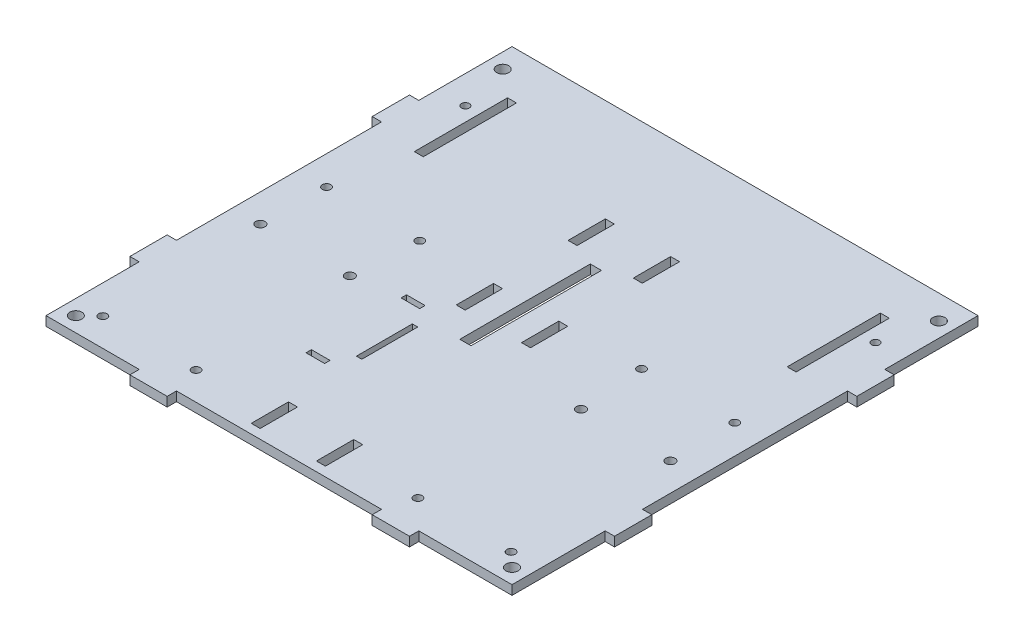
SolidWorks part; units mm, degrees
ref_plane "Front Plane" through (0, 0, 0) normal (0, 0, 1) x (1, 0, 0)
ref_plane "Top Plane" through (0, 0, 0) normal (0, 1, 0) x (1, 0, 0)
ref_plane "Right Plane" through (0, 0, 0) normal (1, 0, 0) x (0, 0, -1)
sketch "Sketch1" plane through (0, 0, 0) normal (0, 1, 0) x (1, 0, 0)
  line L0 (144.9, 25) -> (144.9, 5)
  line L1 (144.9, 5) -> (140.1, 5)
  line L2 (140.1, 25) -> (144.9, 25)
  line L3 (140.1, 5) -> (140.1, 25)
  line L4 (109.9, 5) -> (109.9, 25)
  line L5 (109.9, 25) -> (105.1, 25)
  line L6 (105.1, 25) -> (105.1, 5)
  line L7 (105.1, 5) -> (109.9, 5)
  line L8 (87, 52.4842) -> (97, 52.4842)
  line L9 (97, 55.3842) -> (97, 52.4842)
  line L10 (87, 55.3842) -> (97, 55.3842)
  line L11 (87, 52.4842) -> (87, 55.3842)
  line L12 (105, 64.4342) -> (102.1, 64.4342)
  line L13 (105, 64.4342) -> (105, 94.4342)
  line L14 (102.1, 94.4342) -> (102.1, 64.4342)
  line L15 (102.1, 94.4342) -> (105, 94.4342)
  line L16 (97, 106.3842) -> (97, 103.4842)
  line L17 (97, 106.3842) -> (87, 106.3842)
  line L18 (87, 103.4842) -> (97, 103.4842)
  line L19 (87, 103.4842) -> (87, 106.3842)
  line L20 (109.9, 135) -> (105.1, 135)
  line L21 (109.9, 115) -> (109.9, 135)
  line L22 (105.1, 135) -> (105.1, 115)
  line L23 (105.1, 115) -> (109.9, 115)
  line L24 (144.9, 115) -> (140.1, 115)
  line L25 (140.1, 115) -> (140.1, 135)
  line L26 (144.9, 135) -> (144.9, 115)
  line L27 (140.1, 135) -> (144.9, 135)
  line L28 (227.4, 175) -> (227.4, 225)
  line L29 (222.6, 175) -> (222.6, 225)
  line L30 (227.4, 225) -> (222.6, 225)
  line L31 (222.6, 175) -> (227.4, 175)
  line L32 (125, 100) -> (125, 170) construction
  line L33 (122, 170) -> (128, 170)
  line L34 (122, 170) -> (122, 100)
  line L35 (122, 100) -> (128, 100)
  line L36 (22.6, 225) -> (27.4, 225)
  line L37 (27.4, 225) -> (27.4, 175)
  line L38 (22.6, 175) -> (22.6, 225)
  line L39 (27.4, 175) -> (22.6, 175)
  line L40 (250, 250) -> (0, 250)
  line L41 (0, 250) -> (0, 0)
  line L42 (0, 0) -> (250, 0)
  line L43 (250, 0) -> (250, 250)
  line L44 (128, 170) -> (128, 100)
  dimension "D2" = 22.6
  dimension "D3" = 5.1
  dimension "D4" = 10
  dimension "D5" = 102.1
  dimension "D6" = 2.9
  dimension "D7" = 27.4
  dimension "D8" = 105.1
  dimension "D9" = 4.8
  dimension "D10" = 140.1
  dimension "D11" = 222.6
  dimension "D12" = 5
  dimension "D13" = 25
  dimension "D14" = 52.4842
  dimension "D15" = 250
  dimension "D16" = 64.4342
  dimension "D17" = 103.4842
  dimension "D18" = 94.4342
  dimension "D19" = 115
  dimension "D20" = 50
  dimension "D21" = 6
  dimension "D22" = 70
  dimension "D23" = 175
  dimension "D24" = 125
  dimension "D25" = 250
  dimension "D26" = 80
extrude "Boss-Extrude1" add sketch "Sketch1" along normal blind 5
sketch "Sketch2" plane through (0, 5, 0) normal (0, 1, 0) x (1, 0, 0)
  line L0 (0, 250) -> (0, 0) construction
  line L1 (0, 0) -> (250, 0) construction
  circle A0 centre (15, 100) radius 2.5
  circle A1 centre (63, 100) radius 2.5
  dimension "D1" = 5
  dimension "D2" = 5
  dimension "D3" = 48
  dimension "D4" = 15
  dimension "D5" = 100
extrude "Cut-Extrude1" cut sketch "Sketch2" against normal through all
sketch "Sketch3" plane through (0, 5, 0) normal (0, 1, 0) x (1, 0, 0)
  line L3 (250, 0) -> (250, 250) construction
  circle A0 centre (8, 8) radius 3.25
  circle A1 centre (8, 237) radius 3.25
  dimension "D1" = 6.5
  dimension "D2" = 242
  dimension "D3" = 212
  dimension "D4" = 17
extrude "Cut-Extrude2" cut sketch "Sketch3" against normal through all
ref_plane "Plane1" through (125, 0, 0) normal (-1, 0, 0) x (0, 0, 1)
mirror "Mirror1" about plane through (125, 0, 0) normal (-1, 0, 0) of "Cut-Extrude2"
sketch "Sketch4" plane through (0, 5, 0) normal (0, 1, 0) x (1, 0, 0)
  line L1 (0, 200) -> (-5, 200)
  line L2 (0, 200) -> (0, 180)
  line L3 (0, 180) -> (-5, 180)
  line L4 (-5, 200) -> (-5, 180)
  line L7 (0, 70) -> (-5, 70)
  line L8 (0, 70) -> (0, 50)
  line L9 (0, 50) -> (-5, 50)
  line L10 (-5, 70) -> (-5, 50)
  line L11 (144.9, 5) -> (144.9, 25) construction
  line L12 (50, 0) -> (70, 0)
  line L13 (50, 0) -> (50, -5)
  line L14 (50, -5) -> (70, -5)
  line L15 (70, 0) -> (70, -5)
  line L16 (144.9, 25) -> (140.1, 25) construction
  dimension "D1" = 74.9
  dimension "D2" = 94.9
  dimension "D3" = 144.9
  dimension "D4" = 149.9
  dimension "D5" = 25
  dimension "D6" = 155
  dimension "D7" = 25
extrude "Boss-Extrude2" add sketch "Sketch4" against normal up to vertex (5 mm away)
mirror "Mirror2" about plane through (125, 0, 0) normal (-1, 0, 0) of "Boss-Extrude2"
mirror "Mirror3" about plane through (125, 0, 0) normal (-1, 0, 0) of "Cut-Extrude1"
hole_wizard "Ø4.5 (4.5) Diameter Hole1" positions "Sketch7" profile "Sketch6" hole size "Ø4.5" standard "ISO"
sketch "Sketch7" plane through (0, 5, 0) normal (0, 1, 0) x (1, 0, 0)
  line L0 (255, 200) -> (255, 180) construction
  line L1 (250, 200) -> (255, 200) construction
  point P0 (15.5, 135)
  point P3 (65.5, 135)
  point P6 (65.5, 15)
  point P9 (15.5, 15)
  dimension "D1" = 189.5
  dimension "D2" = 239.5
  dimension "D3" = 65
  dimension "D4" = 185
sketch "Sketch6" plane through (15.5, 5, -135) normal (1, 0, 0) x (0, 0, 1)
  line L0 (0, 0) -> (0, 11.3519)
  line L1 (0, 11.3519) -> (2.25, 10)
  line L2 (2.25, 10) -> (2.25, 0)
  line L5 (2.25, 0) -> (0, 0)
  line L10 (0, 11.3519) -> (-2.25, 10) construction
  line L11 (0, -6.35) -> (0, 107.95) construction
  dimension "Hole Dia." = 4.5
  dimension "Hole Depth" = 10
  dimension "Drill Angle" = 118
mirror "Mirror4" about plane through (125, 0, 0) normal (-1, 0, 0) of "Ø4.5 (4.5) Diameter Hole1"
sketch "Sketch9" plane through (0, 0, 0) normal (0, -1, 0) x (1, 0, 0)
  line L0 (105, -175) -> (110, -175) construction
  line L1 (105.1, -175) -> (109.9, -175)
  line L2 (105.1, -175) -> (105.1, -195)
  line L3 (105.1, -195) -> (109.9, -195)
  line L4 (109.9, -175) -> (109.9, -195)
  line L5 (105, -195) -> (110, -195) construction
  line L6 (105, -175) -> (105, -195) construction
  dimension "D1" = 4.8
  dimension "D2" = 0.1
extrude "Cut-Extrude3" cut sketch "Sketch9" against normal through all
mirror "Mirror5" about plane through (125, 0, 0) normal (-1, 0, 0) of "Cut-Extrude3"
sketch "Sketch10" plane through (0, 0, 0) normal (0, -1, 0) x (1, 0, 0)
  line L0 (0, -250) -> (0, 10) construction
  line L1 (250, -250) -> (0, -250) construction
  line L2 (250, -250) -> (250, 10) construction
  circle A0 centre (15, -210) radius 2.1
  circle A1 centre (235, -210) radius 2.1
  dimension "D1" = 4.2
  dimension "D2" = 15
  dimension "D3" = 40
  dimension "D4" = 15
extrude "Cut-Extrude4" cut sketch "Sketch10" against normal blind 5
